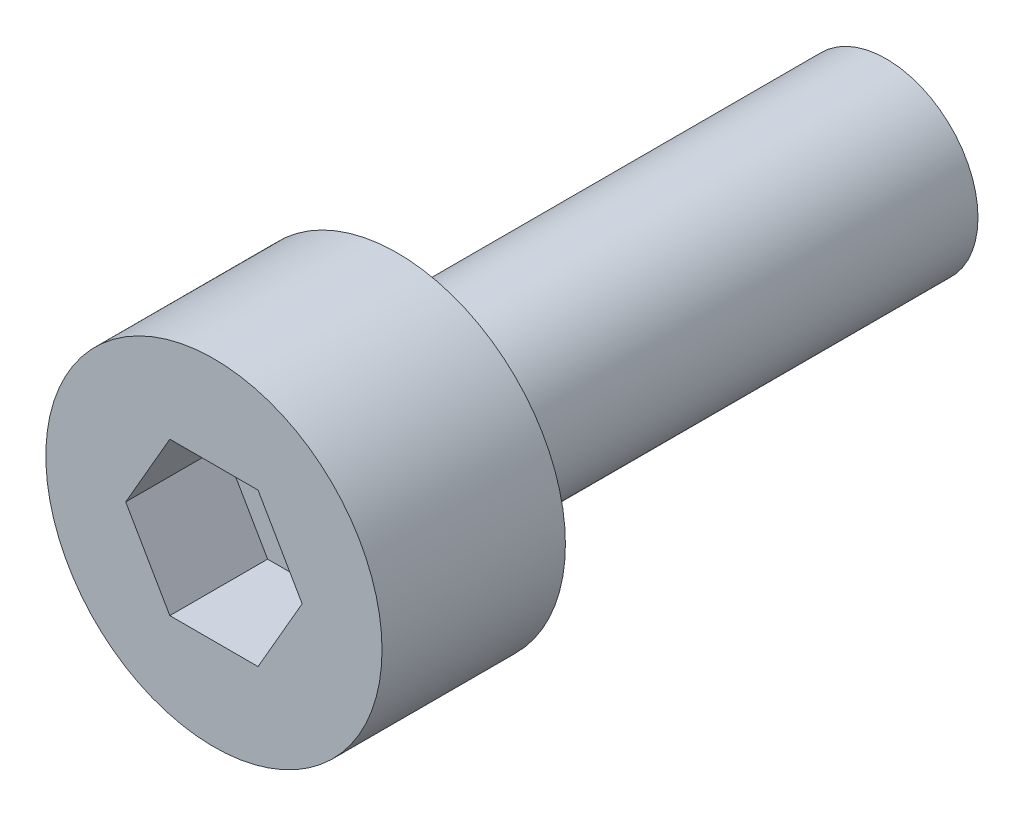
SolidWorks part; units mm, degrees
ref_plane "Front Plane" through (0, 0, 0) normal (0, 0, 1) x (1, 0, 0)
ref_plane "Top Plane" through (0, 0, 0) normal (0, 1, 0) x (1, 0, 0)
ref_plane "Right Plane" through (0, 0, 0) normal (1, 0, 0) x (0, 0, -1)
sketch "Sketch1" plane through (0, 0, 0) normal (0, 0, 1) x (1, 0, 0)
  circle A0 centre (0, 0) radius 1.5
extrude "Shank" add sketch "Sketch1" along normal blind 8
ref_plane "Plane_z8" through (0, 0, 8) normal (0, 0, 1) x (1, 0, 0)
sketch "Sketch2" plane through (0, 0, 8) normal (0, 0, 1) x (1, 0, 0)
  circle A0 centre (0, 0) radius 2.75
extrude "Head" add sketch "Sketch2" along normal blind 3
ref_plane "Plane_z9_4" through (0, 0, 9.4) normal (0, 0, 1) x (1, 0, 0)
sketch "Sketch3" plane through (0, 0, 9.4) normal (0, 0, 1) x (1, 0, 0)
  line L0 (1.4434, 0) -> (0.7217, 1.25)
  line L1 (0.7217, 1.25) -> (-0.7217, 1.25)
  line L2 (-0.7217, 1.25) -> (-1.4434, 0)
  line L3 (-1.4434, 0) -> (-0.7217, -1.25)
  line L4 (-0.7217, -1.25) -> (0.7217, -1.25)
  line L5 (0.7217, -1.25) -> (1.4434, 0)
extrude "Socket" cut sketch "Sketch3" along normal blind 1.6
